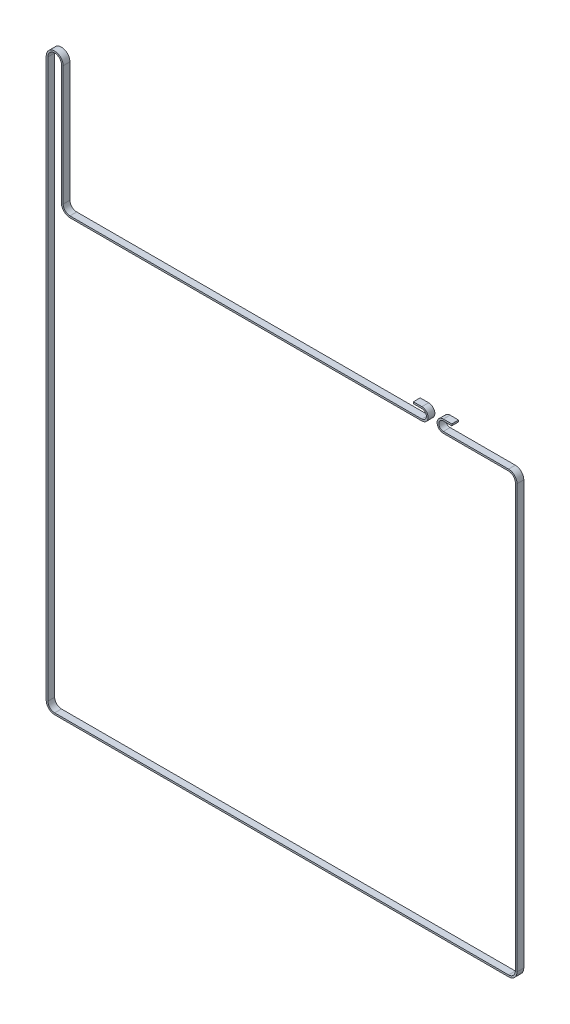
SolidWorks part; units mm, degrees
ref_plane "Front Plane" through (0, 0, 0) normal (0, 0, 1) x (1, 0, 0)
ref_plane "Top Plane" through (0, 0, 0) normal (0, 1, 0) x (1, 0, 0)
ref_plane "Right Plane" through (0, 0, 0) normal (1, 0, 0) x (0, 0, -1)
sketch "Sketch1" plane through (0, 0, 0) normal (0, 0, 1) x (1, 0, 0)
  line L0 (-6, 0) -> (-6, -494.15)
  line L1 (6, 0) -> (6, -106.1498)
  line L2 (13.5, -113.6498) -> (325.2278, -113.6498)
  line L3 (0, -500.15) -> (402, -500.15)
  line L4 (408, -494.15) -> (408, -119.6498)
  line L5 (402, -113.6498) -> (344.2278, -113.6498)
  line L6 (13.5, -112.1498) -> (325.2278, -112.1498)
  line L7 (7.5, 0) -> (7.5, -106.1498)
  line L8 (-7.5, 0) -> (-7.5, -494.15)
  line L9 (0, -501.65) -> (402, -501.65)
  line L10 (409.5, -494.15) -> (409.5, -119.6498)
  line L11 (402, -112.1498) -> (344.2278, -112.1498)
  line L14 (317.7278, -102.6498) -> (317.7278, -104.1498)
  line L15 (351.7278, -102.6498) -> (351.7278, -104.1498)
  line L16 (317.7278, -102.6498) -> (325.2278, -102.6498)
  line L17 (317.7278, -104.1498) -> (317.7278, -111.1498) construction
  line L20 (317.7278, -104.1498) -> (325.2278, -104.1498)
  line L21 (351.7278, -104.1498) -> (351.7278, -111.1498) construction
  line L22 (351.7278, -102.6498) -> (344.2278, -102.6498)
  line L23 (351.7278, -104.1498) -> (344.2278, -104.1498)
  arc A1 (6, 0) -> (-6, 0) centre (0, 0) ccw
  arc A2 (6, -106.1498) -> (13.5, -113.6498) centre (13.5, -106.1498) ccw
  arc A3 (-6, -494.15) -> (0, -500.15) centre (0, -494.15) ccw
  arc A4 (402, -500.15) -> (408, -494.15) centre (402, -494.15) ccw
  arc A5 (408, -119.6498) -> (402, -113.6498) centre (402, -119.6498) ccw
  arc A6 (7.5, -106.1498) -> (13.5, -112.1498) centre (13.5, -106.1498) ccw
  arc A7 (7.5, 0) -> (-7.5, 0) centre (0, 0) ccw
  arc A8 (-7.5, -494.15) -> (0, -501.65) centre (0, -494.15) ccw
  arc A9 (402, -501.65) -> (409.5, -494.15) centre (402, -494.15) ccw
  arc A10 (409.5, -119.6498) -> (402, -112.1498) centre (402, -119.6498) ccw
  arc A11 (325.2278, -104.1498) -> (325.2278, -112.1498) centre (325.2278, -108.1498) cw
  arc A12 (325.2278, -102.6498) -> (325.2278, -113.6498) centre (325.2278, -108.1498) cw
  arc A13 (344.2278, -104.1498) -> (344.2278, -112.1498) centre (344.2278, -108.1498) ccw
  arc A14 (344.2278, -102.6498) -> (344.2278, -113.6498) centre (344.2278, -108.1498) ccw
  circle A15 centre (0, -494.15) radius 1.5 construction
  circle A16 centre (0, -494.15) radius 1.65 construction
  circle A17 centre (402, -494.15) radius 1.65 construction
  circle A18 centre (13.5, -106.1498) radius 1.5 construction
  dimension "D1" = 12
  dimension "D2" = 6
  dimension "D6" = 1.5
  dimension "D4" = 7.5
  dimension "D5" = 7.5
  dimension "D3" = 1.5
  dimension "D7" = 8
  dimension "D8" = 8
  dimension "D10" = 1.5
extrude "Boss-Extrude1" add sketch "Sketch1" along normal blind 6
